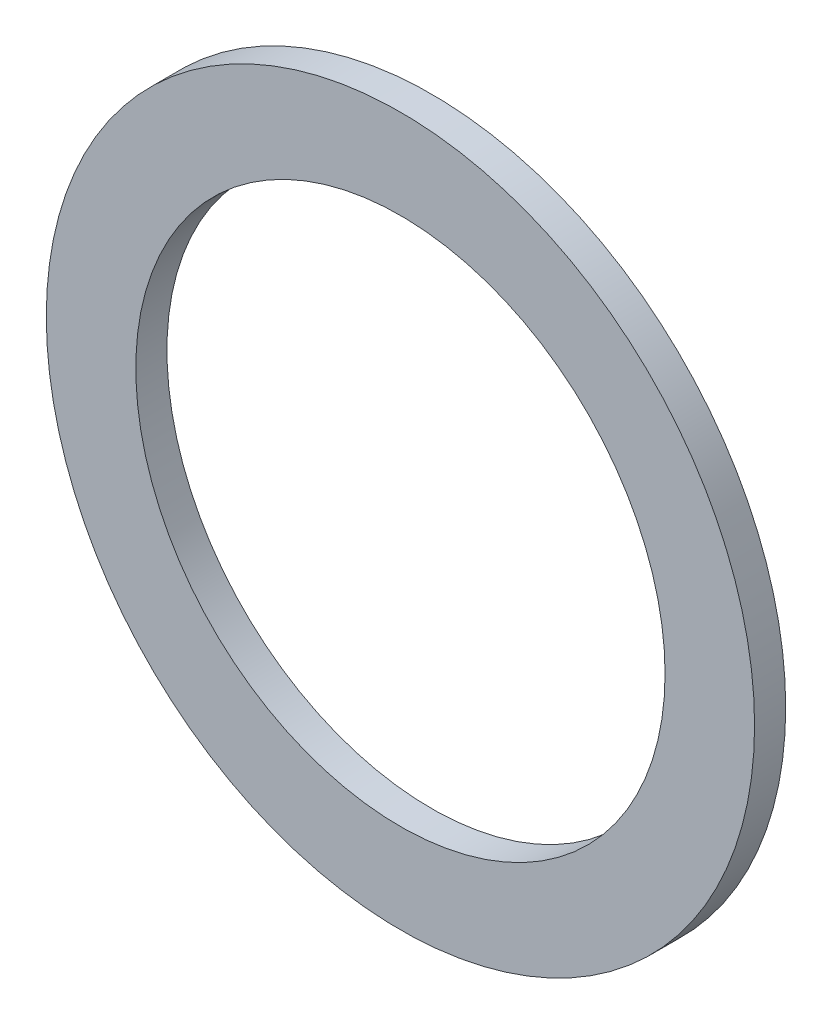
SolidWorks part; units mm, degrees
material "橡膠"
ref_plane "前基準面" through (0, 0, 0) normal (0, 0, 1) x (1, 0, 0)
ref_plane "上基準面" through (0, 0, 0) normal (0, 1, 0) x (1, 0, 0)
ref_plane "右基準面" through (0, 0, 0) normal (1, 0, 0) x (0, 0, -1)
sketch "草圖1" plane through (0, 0, 0) normal (0, 0, 1) x (1, 0, 0)
  circle A0 centre (0, 0) radius 17
  circle A1 centre (0, 0) radius 22.75
  dimension "D1" = 34
  dimension "D2" = 45.5
extrude "伸長1" add sketch "草圖1" along normal blind 2
